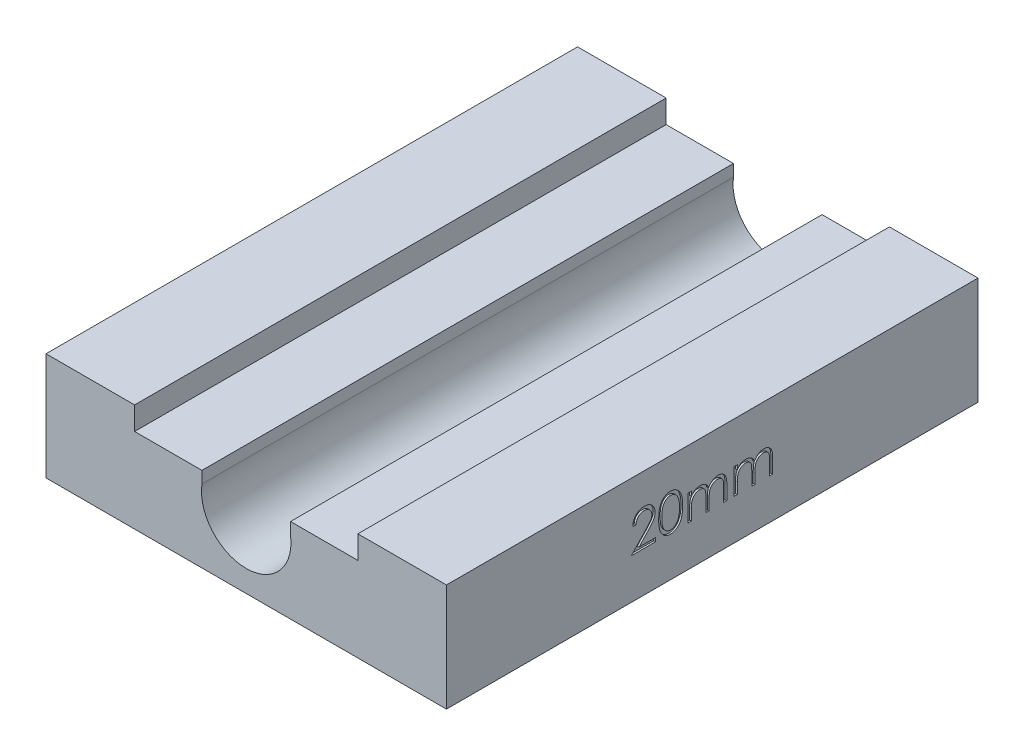
SolidWorks part; units mm, degrees
ref_plane "Front Plane" through (0, 0, 0) normal (0, 0, 1) x (1, 0, 0)
ref_plane "Top Plane" through (0, 0, 0) normal (0, 1, 0) x (1, 0, 0)
ref_plane "Right Plane" through (0, 0, 0) normal (1, 0, 0) x (0, 0, -1)
sketch "Sketch1" plane through (0, 0, 0) normal (0, 0, 1) x (1, 0, 0)
  line L0 (0, 0) -> (0, 14.2836) construction
  line L1 (0, 14.2836) -> (-10, 4.2836)
  line L2 (0, 14.2836) -> (10, 4.2836)
  line L3 (-10, 4.2836) -> (-25, 4.2836)
  line L4 (-25, 4.2836) -> (-25, 24.2836)
  line L5 (-25, 24.2836) -> (25, 24.2836)
  line L6 (25, 24.2836) -> (25, 4.2836)
  line L7 (25, 4.2836) -> (10, 4.2836)
  line L8 (-45.2, 9.2836) -> (-45.2, -15)
  line L9 (-45.2, -15) -> (45.2, -15)
  line L10 (45.2, -15) -> (45.2, 9.2836)
  line L11 (45.2, 9.2836) -> (25.2, 9.2836)
  line L12 (25.2, 9.2836) -> (25.2, 4.0836)
  line L13 (-25.2, 4.0836) -> (-10, 4.0836)
  line L14 (-45.2, 9.2836) -> (-25.2, 9.2836)
  line L15 (-25.2, 9.2836) -> (-25.2, 4.0836)
  line L16 (25.2, 4.0836) -> (10, 4.0836)
  line L17 (-10, 4.0836) -> (-10, 1.4177)
  line L18 (10, 4.0836) -> (10, 1.4177)
  circle A0 centre (0, 0) radius 10.1
  dimension "D12" = 20.2
  dimension "D1" = 45
  dimension "D2" = 10
  dimension "D3" = 20
  dimension "D4" = 50
  dimension "D5" = 25
  dimension "D6" = 5
  dimension "D7" = 0.2
  dimension "D8" = 0.2
  dimension "D9" = 5
  dimension "D10" = 20
  dimension "D11" = 20
  dimension "D13" = 15
  dimension "D14" = 0.2
  dimension "D15" = 0.2
extrude "Boss-Extrude1" add sketch "Sketch1" along normal blind 120 contours A0 L17 L13 L15 L14 L8 L9 L10 L11 L12 L16 L18
sketch "Sketch2" plane through (45.2, 0, 0) normal (1, 0, 0) x (0, 0, -1)
  text T0 "20mm" font "Century Gothic" height 8
extrude "Cut-Extrude1" cut sketch "Sketch2" against normal blind 0.4
